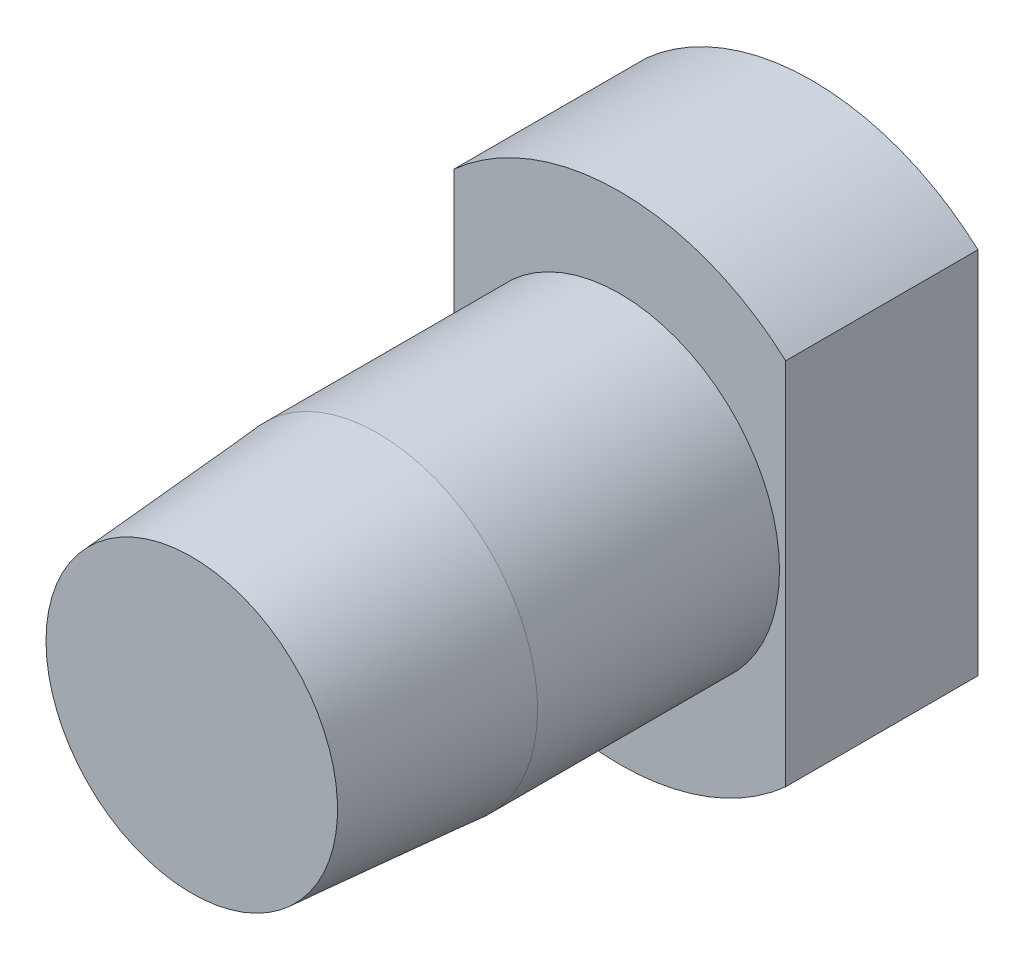
SolidWorks part; units mm, degrees
material "K1045"
ref_plane "Front Plane" through (0, 0, 0) normal (0, 0, 1) x (1, 0, 0)
ref_plane "Top Plane" through (0, 0, 0) normal (0, 1, 0) x (1, 0, 0)
ref_plane "Right Plane" through (0, 0, 0) normal (1, 0, 0) x (0, 0, -1)
sketch "Sketch1" plane through (0, 0, 0) normal (1, 0, 0) x (0, 0, -1)
  line L0 (0, 0) -> (17.8259, 0) construction
  line L1 (0, 0) -> (0, 2.35)
  line L2 (0, 2.35) -> (3, 2.575)
  line L3 (3, 2.575) -> (6.9, 2.575)
  line L4 (6.9, 2.575) -> (6.9, 4)
  line L5 (6.9, 4) -> (10, 4)
  line L6 (10, 4) -> (10, 2.25)
  line L7 (10, 2.25) -> (7.75, 0)
  line L8 (0, 0) -> (7.75, 0)
  dimension "D1" = 4.7
  dimension "D2" = 5.15
  dimension "D3" = 5.15
  dimension "D4" = 3
  dimension "D5" = 3.1
  dimension "D6" = 10
  dimension "D7" = 4.5
  dimension "D8" = 8
  dimension "D9" = 45
revolve "Revolve1" add sketch "Sketch1" angle 360 about L0
sketch "Sketch2" plane through (0, 0, -10) normal (0, 0, -1) x (-1, 0, 0)
  line L0 (0, 0) -> (0, 5.3607) construction
  line L1 (2.675, 4.2162) -> (5.2597, 4.2162)
  line L2 (2.675, 4.2162) -> (2.675, -4.2162)
  line L3 (2.675, -4.2162) -> (5.2597, -4.2162)
  line L4 (5.2597, 4.2162) -> (5.2597, -4.2162)
  line L5 (0, 0) -> (7.2121, 0) construction
  line L6 (-5.2597, 4.2162) -> (-5.2597, -4.2162)
  line L7 (-2.675, -4.2162) -> (-5.2597, -4.2162)
  line L8 (-2.675, 4.2162) -> (-2.675, -4.2162)
  line L9 (-2.675, 4.2162) -> (-5.2597, 4.2162)
  dimension "D1" = 8.4324
  dimension "D2" = 5.35
  dimension "D3" = 10.5195
extrude "Cut-Extrude1" cut sketch "Sketch2" against normal through all
